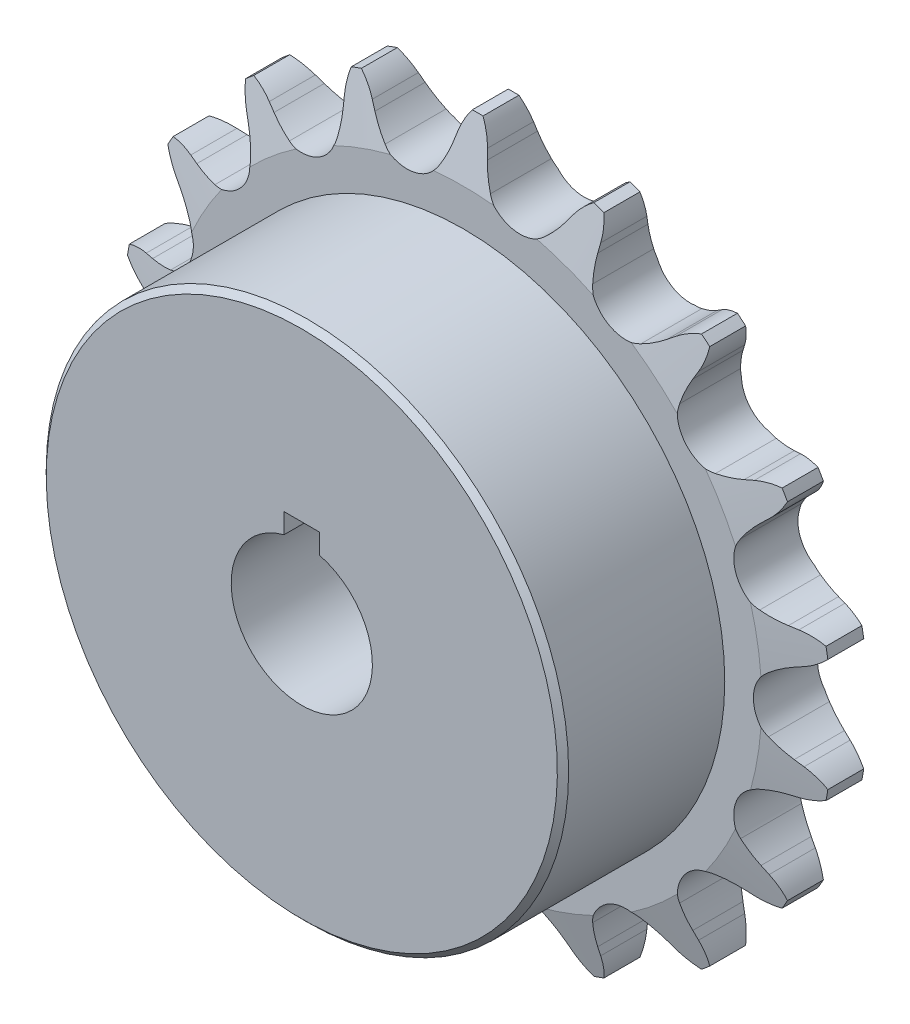
SolidWorks part; units mm, degrees
material "AISI 1045 Steel, cold drawn"
ref_plane "Front Plane" through (0, 0, 0) normal (0, 0, 1) x (1, 0, 0)
ref_plane "Top Plane" through (0, 0, 0) normal (0, 1, 0) x (1, 0, 0)
ref_plane "Right Plane" through (0, 0, 0) normal (1, 0, 0) x (0, 0, -1)
sketch "Sketch2" plane through (0, 0, 0) normal (0, 0, 1) x (1, 0, 0)
  line L0 (6.35, -36.0126) -> (0, 0) construction
  line L1 (0, 0) -> (18.2841, -31.669) construction
  line L2 (0, 0) -> (-6.35, -36.0126) construction
  line L3 (6.35, -36.0126) -> (18.2841, -31.669) construction
  line L4 (6.35, -36.0126) -> (-6.35, -36.0126) construction
  line L5 (11.2734, -35.8522) -> (10.7495, -35.0591)
  line L6 (6.35, -36.0126) -> (0, -37.1323) construction
  line L7 (1.6687, -37.5458) -> (1.8897, -36.6213)
  line L8 (0, -36.0126) -> (0, -39.8226) construction
  line L9 (8.9984, -33.0367) -> (2.1353, -40.7487) construction
  line L10 (0, 0) -> (0, -36.0126) construction
  line L11 (10.7495, -35.0591) -> (2.1353, -40.7487) construction
  line L12 (0, -39.8226) -> (0, -40.5919) construction
  line L13 (16.7756, -32.218) -> (11.2734, -35.8522) construction
  circle A0 centre (0, 0) radius 39.8226 construction
  circle A1 centre (0, 0) radius 36.5682 construction
  arc A2 (-5.6061, -42.5503) -> (19.821, -38.0668) centre (0, 0) ccw
  circle A3 centre (0, 0) radius 40.5919 construction
  circle A4 centre (6.35, -36.0126) radius 3.9624 construction
  arc A7 (8.9984, -33.0367) -> (2.8435, -34.122) centre (6.35, -36.0126) ccw
  circle A8 centre (6.35, -36.0126) radius 3.9837 construction
  arc A9 (11.2734, -35.8522) -> (19.821, -38.0668) centre (16.7756, -32.218) ccw
  arc A10 (10.7495, -35.0591) -> (8.9984, -33.0367) centre (2.1353, -40.7487) ccw
  arc A11 (1.6687, -37.5458) -> (-5.6061, -42.5503) centre (-4.7447, -36.0126) cw
  arc A12 (1.8897, -36.6213) -> (2.8435, -34.122) centre (11.9303, -39.0215) cw
  dimension "D1" = 3.9837
  dimension "R" = 3.9837
  dimension "Pitch" = 12.7
sketch "Sketch0" plane through (0, 0, 0) normal (0, 0, 1) x (1, 0, 0)
  line L0 (-12.7, 0) -> (12.7, 0) construction
  circle A0 centre (0, 0) radius 7.9375 construction
  circle A1 centre (0, 0) radius 39.878 construction
  circle A2 centre (0, 0) radius 19.05 construction
  circle A3 centre (0, 0) radius 29.3688 construction
  point P9 (0, 0)
  dimension "OD" = 79.756
  dimension "ID" = 15.875
  dimension "Maximum Shaft Diameter" = 38.1
  dimension "Hub Diameter" = 58.7375
  dimension "Overall Width" = 25.4
sketch "Sketch1" plane through (0, 0, 0) normal (1, 0, 0) x (0, 0, -1)
  line L0 (3.6068, 0) -> (-3.6068, 0)
  line L1 (-3.6068, 0) -> (-3.6068, 33.528)
  line L2 (-3.6068, 33.528) -> (-2.0193, 39.878)
  line L3 (-2.0193, 39.878) -> (2.0193, 39.878)
  line L4 (2.0193, 39.878) -> (3.6068, 33.528)
  line L5 (3.6068, 33.528) -> (3.6068, 0)
  line L7 (0, 39.878) -> (0, 0) construction
  line L8 (-3.6068, 33.528) -> (3.6068, 33.528) construction
  line L9 (0, 39.8226) -> (0, -39.8226) construction
  line L10 (-3.6068, 33.528) -> (-3.6068, 39.878) construction
  line L11 (-3.6068, 39.878) -> (-2.0193, 39.878) construction
  line L12 (2.0193, 39.878) -> (3.6068, 39.878) construction
  line L13 (3.6068, 39.878) -> (3.6068, 33.528) construction
  line L22 (3.6068, 0) -> (-21.7932, 0) construction
  line L24 (-3.6068, 0) -> (-3.6068, 29.6476) construction
  dimension "D1" = 25.4
revolve "Revolve1" add sketch "Sketch1" angle 360 mid plane about L0
extrude "Cut-Extrude1" cut sketch "Sketch2" against normal through all and the other way through all
pattern_circular "CirPattern1" count 18 over 360 about axis through (0, 0, 0) along (0, 0, 1) of "Cut-Extrude1"
sketch "Sketch3" plane through (0, 0, 0) normal (0, 0, 1) x (1, 0, 0)
  circle A0 centre (0, 0) radius 7.9375 construction
  circle A1 centre (0, 0) radius 29.3688
  circle A2 centre (0, 0) radius 39.878 construction
  circle A3 centre (0, 0) radius 7.9375 construction
  circle A4 centre (0, 0) radius 39.878 construction
  circle A5 centre (0, 0) radius 29.3687 construction
extrude "Boss-Extrude1" add sketch "Sketch3" along normal up to vertex (21.7932 mm away) from surface at 3.6068 starting at face at (0, 0, 3.6068)
sketch "Sketch4" plane through (0, 0, 0) normal (0, 0, 1) x (1, 0, 0)
  circle A1 centre (0, 0) radius 7.9375
  circle A2 centre (0, 0) radius 7.9375 construction
extrude "Cut-Extrude2" cut sketch "Sketch4" along normal through all and the other way through all
sketch "Sketch5" plane through (0, 0, 0) normal (1, 0, 0) x (0, 0, -1)
  line L0 (-21.7932, 29.3687) -> (-21.7932, 28.7338)
  line L1 (-3.6068, 39.878) -> (-9.017, 39.878)
  line L2 (-3.6068, 39.878) -> (-3.6068, 29.6476)
  line L3 (-3.6068, 29.6476) -> (-9.017, 29.6476)
  line L4 (-9.017, 39.878) -> (-9.017, 29.6476)
  line L9 (-21.7932, 28.7338) -> (-21.1582, 29.3688)
  line L10 (-21.1582, 29.3688) -> (-21.7932, 29.3687)
  dimension "C" = 0.635
  dimension "D3" = 5.4102
revolve "Cut-Revolve1" cut sketch "Sketch5" angle 360 mid plane about L22
sketch "Sketch6" plane through (0, 0, -3.6068) normal (0, 0, -1) x (-1, 0, 0)
  line L0 (-2, 7.6814) -> (-2, 9.9375)
  line L1 (-2, 9.9375) -> (2, 9.9375)
  line L2 (2, 9.9375) -> (2, 7.6814)
  line L3 (0, 9.9375) -> (0, 7.9375) construction
  circle A0 centre (0, 0) radius 7.9375 construction
  arc A1 (2, 7.6814) -> (-2, 7.6814) centre (0, 0) ccw
  point P1 (3.156, 14.9339)
  point P8 (-3.4025, 12.5181)
  point P9 (3.2546, 11.1869)
  point P12 (0, 9.9375)
  dimension "D1" = 2
  dimension "D2" = 4
extrude "Cut-Extrude3" cut sketch "Sketch6" against normal through all
equation "\"360/N@Sketch2\" = 360 / \"Teeth@CirPattern1\""
equation "\"Ds@Sketch2\" = 1.005 * \"Dr@Sketch2\" + 0.003"
equation "\"R@Sketch2\" = 1 / 2 * \"Ds@Sketch2\""
equation "\"A@Sketch2\" = 35 +  ( 60 / \"Teeth@CirPattern1\" ) "
equation "\"B@Sketch2\" = 18 -  ( 56 / \"Teeth@CirPattern1\" ) "
equation "\"ac@Sketch2\" = 0.8 * \"Dr@Sketch2\""
equation "\"ab@Sketch2\" = 1.4 * \"Dr@Sketch2\""
equation "\"J@Sketch2\" = 0.3 * \"Pitch@Sketch2\""
equation "\"h@Sketch1\" = \"Pitch@Sketch2\" / 2"
equation "\"g@Sketch1\" = \"h@Sketch1\" / 4"
equation "\"MHD@Sketch1\" = \"Pitch@Sketch2\" *  ( cotan ( 180 / \"Teeth@CirPattern1\" )  - 1 )  - 0.030"
equation "\"D3@Sketch5\" = \"t@Sketch1\" * 3 / 4"
equation "\"D1@Sketch1\"=\"Overall Width@Sketch0\""
equation "\"Keyway Width\" = 4mm"
equation "\"Keyway Height\"= 2mm"
equation "\"D1@Sketch6\"=\"Keyway Height\""
equation "\"D2@Sketch6\"=\"Keyway Width\""
